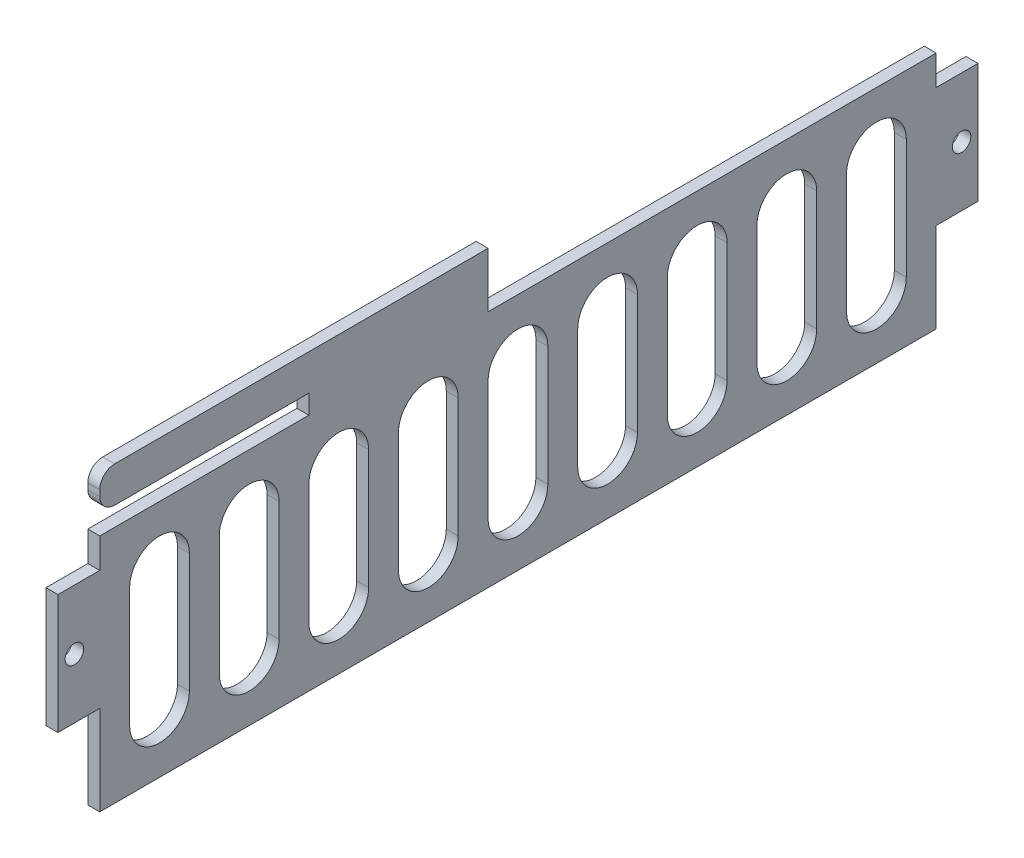
SolidWorks part; units mm, degrees
material "A-玻璃纤维"
ref_plane "前视基准面" through (0, 0, 0) normal (0, 0, 1) x (1, 0, 0)
ref_plane "上视基准面" through (0, 0, 0) normal (0, 1, 0) x (1, 0, 0)
ref_plane "右视基准面" through (0, 0, 0) normal (1, 0, 0) x (0, 0, -1)
sketch "草图1" plane through (0, 0, 0) normal (1, 0, 0) x (0, 0, -1)
  line L1 (-70, 20) -> (70, 20)
  line L2 (-70, 20) -> (-70, -20)
  line L3 (-70, -20) -> (70, -20)
  line L4 (70, 20) -> (70, -20)
  line L5 (0, -20) -> (0, 20) construction
  line L6 (-70, 0) -> (70, 0) construction
  line L7 (-70, 15) -> (-77, 15)
  line L8 (-70, 15) -> (-70, -5)
  line L9 (-70, -5) -> (-77, -5)
  line L10 (-77, 15) -> (-77, -5)
  line L11 (-35, 20) -> (-5, 20)
  line L12 (-35, 20) -> (-35, 23.2)
  line L13 (-35, 23.2) -> (-5, 23.2)
  line L14 (-5, 20) -> (-5, 23.2)
  line L15 (-5, 23.2) -> (-67.5, 23.2)
  line L16 (-5, 23.2) -> (-5, 29.2)
  line L17 (-5, 29.2) -> (-67.5, 29.2)
  line L18 (-70, 25.7) -> (-70, 26.7)
  line L19 (70, 15) -> (77, 15)
  line L20 (70, 15) -> (70, -5)
  line L21 (70, -5) -> (77, -5)
  line L22 (77, 15) -> (77, -5)
  arc A0 (-67.5, 23.2) -> (-70, 25.7) centre (-67.5, 25.7) cw
  arc A1 (-67.5, 29.2) -> (-70, 26.7) centre (-67.5, 26.7) ccw
  point P0 (0, 0)
  point P20 (-70, 23.2)
  dimension "D11" = 2.5
  dimension "D1" = 140
  dimension "D2" = 40
  dimension "D3" = 20
  dimension "D4" = 7
  dimension "D5" = 5
  dimension "D6" = 30
  dimension "D7" = 35
  dimension "D8" = 3.2
  dimension "D9" = 6
  dimension "D10" = 65
  dimension "D12" = 20
  dimension "D13" = 7
  dimension "D14" = 5
extrude "凸台-拉伸1" add sketch "草图1" along normal blind 2 contours L4 L1 L2 L3 | L7 L10 L9 L2 | L17 A1 L18 A0 L15 L13 L16 | L1 L14 L13 L12 | L22 L19 L4 L21
sketch "草图2" plane through (2, 0, 0) normal (1, 0, 0) x (0, 0, -1)
  line L0 (-60, -10) -> (-60, 10) construction
  line L1 (-65, -10) -> (-65, 10)
  line L2 (-55, -10) -> (-55, 10)
  line L3 (-70, -5) -> (-70, -20) construction
  line L4 (-45, -10) -> (-45, 10) construction
  line L5 (-50, -10) -> (-50, 10)
  line L6 (-40, -10) -> (-40, 10)
  line L7 (-30, -10) -> (-30, 10) construction
  line L8 (-35, -10) -> (-35, 10)
  line L9 (-25, -10) -> (-25, 10)
  line L10 (-15, -10) -> (-15, 10) construction
  line L11 (-20, -10) -> (-20, 10)
  line L12 (-10, -10) -> (-10, 10)
  line L13 (0, -10) -> (0, 10) construction
  line L14 (-5, -10) -> (-5, 10)
  line L15 (5, -10) -> (5, 10)
  line L16 (15, -10) -> (15, 10) construction
  line L17 (10, -10) -> (10, 10)
  line L18 (20, -10) -> (20, 10)
  line L19 (30, -10) -> (30, 10) construction
  line L20 (25, -10) -> (25, 10)
  line L21 (35, -10) -> (35, 10)
  line L22 (45, -10) -> (45, 10) construction
  line L23 (40, -10) -> (40, 10)
  line L24 (50, -10) -> (50, 10)
  line L25 (60, -10) -> (60, 10) construction
  line L26 (55, -10) -> (55, 10)
  line L27 (65, -10) -> (65, 10)
  arc A0 (-65, -10) -> (-55, -10) centre (-60, -10) ccw
  arc A1 (-55, 10) -> (-65, 10) centre (-60, 10) ccw
  arc A2 (-50, -10) -> (-40, -10) centre (-45, -10) ccw
  arc A3 (-40, 10) -> (-50, 10) centre (-45, 10) ccw
  arc A4 (-35, -10) -> (-25, -10) centre (-30, -10) ccw
  arc A5 (-25, 10) -> (-35, 10) centre (-30, 10) ccw
  arc A6 (-20, -10) -> (-10, -10) centre (-15, -10) ccw
  arc A7 (-10, 10) -> (-20, 10) centre (-15, 10) ccw
  arc A8 (-5, -10) -> (5, -10) centre (0, -10) ccw
  arc A9 (5, 10) -> (-5, 10) centre (0, 10) ccw
  arc A10 (10, -10) -> (20, -10) centre (15, -10) ccw
  arc A11 (20, 10) -> (10, 10) centre (15, 10) ccw
  arc A12 (25, -10) -> (35, -10) centre (30, -10) ccw
  arc A13 (35, 10) -> (25, 10) centre (30, 10) ccw
  arc A14 (40, -10) -> (50, -10) centre (45, -10) ccw
  arc A15 (50, 10) -> (40, 10) centre (45, 10) ccw
  arc A16 (55, -10) -> (65, -10) centre (60, -10) ccw
  arc A17 (65, 10) -> (55, 10) centre (60, 10) ccw
  point P2 (-60, 0)
  point P9 (-45, 0)
  point P20 (-30, 0)
  point P27 (-15, 0)
  point P34 (0, 0)
  point P41 (15, 0)
  point P48 (30, 0)
  point P55 (45, 0)
  point P62 (60, 0)
  dimension "D1" = 5
  dimension "D2" = 10
  dimension "D3" = 20
  dimension "D4" = 9
extrude "切除-拉伸1" cut sketch "草图2" against normal blind 3
sketch "草图3" plane through (2, 0, 0) normal (1, 0, 0) x (0, 0, -1)
  line L0 (-77, 15) -> (-77, -5) construction
  line L3 (-70, 15) -> (-77, 15) construction
  line L4 (0, 45.0601) -> (0, -46.0877) construction
  circle A0 centre (-74.25, 5) radius 1.55
  circle A1 centre (74.25, 5) radius 1.55
  dimension "D1" = 3.1
  dimension "D2" = 2.75
  dimension "D3" = 10
extrude "切除-拉伸2" cut sketch "草图3" against normal blind 3
